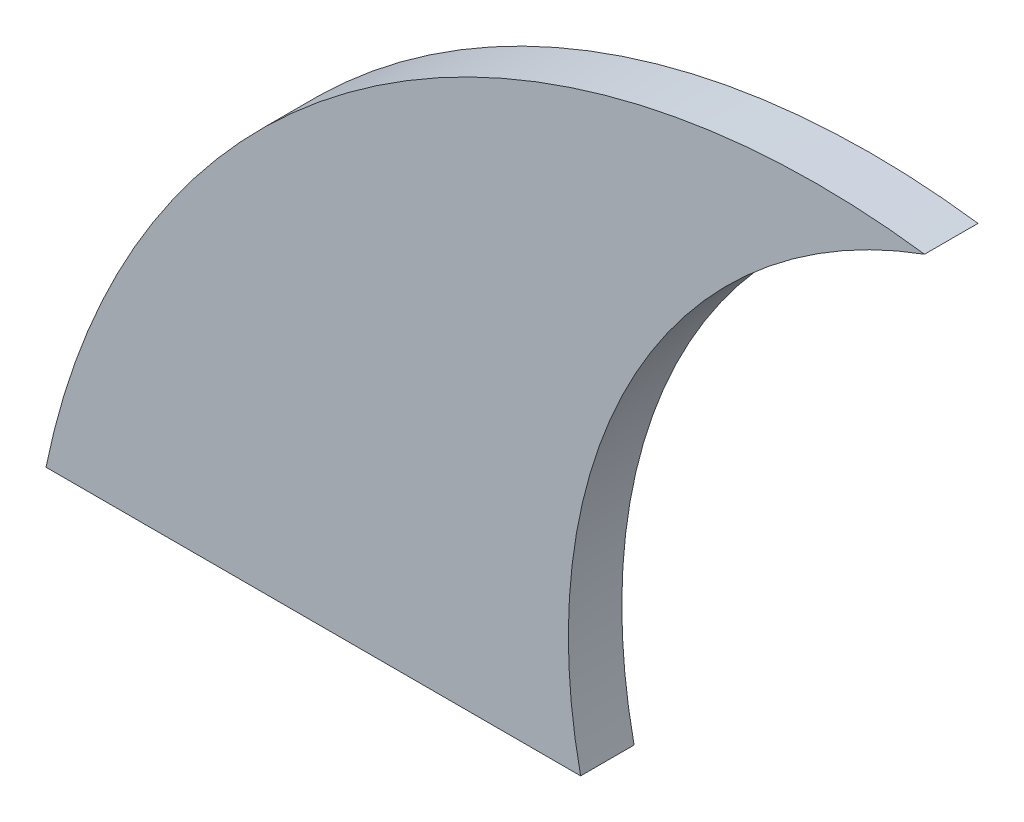
SolidWorks part; units mm, degrees
ref_plane "Front" through (0, 0, 0) normal (0, 0, 1) x (1, 0, 0)
ref_plane "Top" through (0, 0, 0) normal (0, 1, 0) x (1, 0, 0)
ref_plane "Right" through (0, 0, 0) normal (1, 0, 0) x (0, 0, -1)
sketch "Sketch1" plane through (0, 0, 0) normal (0, 0, 1) x (1, 0, 0)
  line L0 (0, 0) -> (30, 0)
  arc A0 (0, 0) -> (49.2982, 35) centre (43.3129, -8.7884) cw
  arc A1 (30, 0) -> (49.2982, 35) centre (59.713, 6.4372) cw
  dimension "D1" = 30
  dimension "D2" = 35
extrude "Boss-Extrude1" add sketch "Sketch1" along normal blind 3 contours A0 A1 L0
